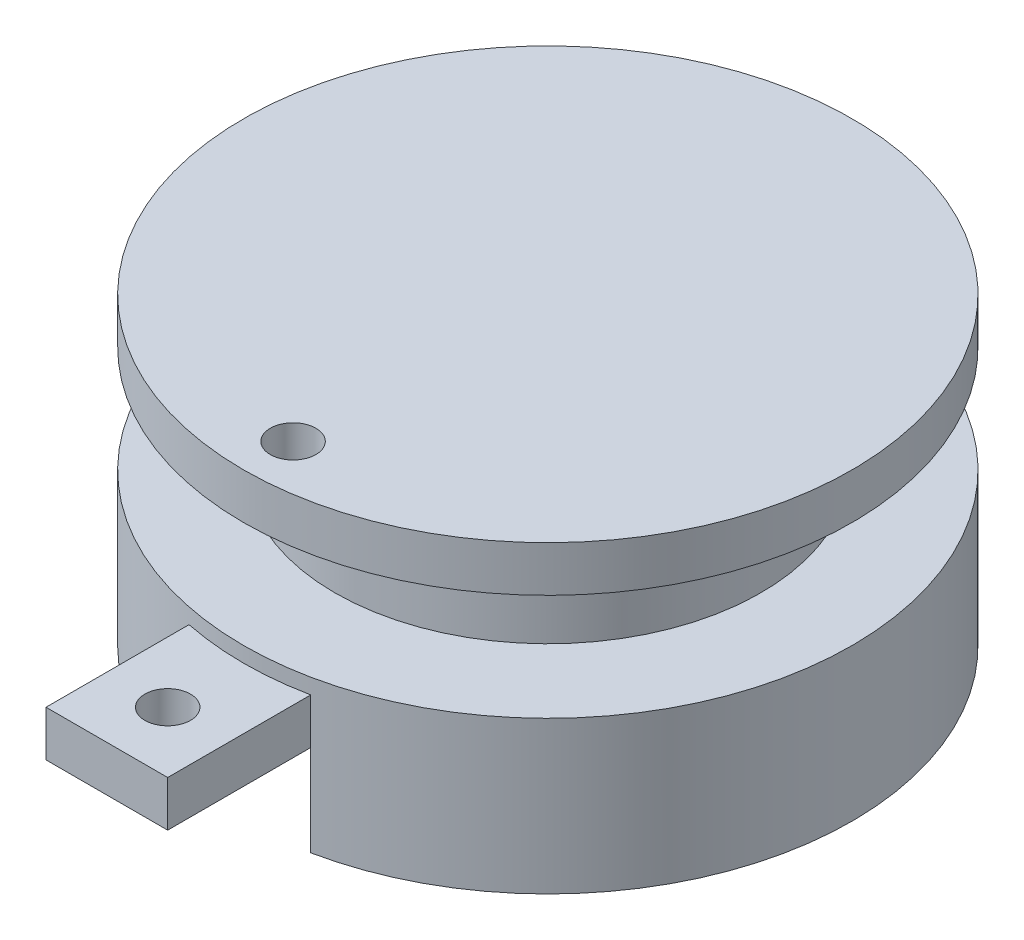
SolidWorks part; units mm, degrees
ref_plane "Front Plane" through (0, 0, 0) normal (0, 0, 1) x (1, 0, 0)
ref_plane "Top Plane" through (0, 0, 0) normal (0, 1, 0) x (1, 0, 0)
ref_plane "Right Plane" through (0, 0, 0) normal (1, 0, 0) x (0, 0, -1)
sketch "Sketch1" plane through (0, 0, 0) normal (0, 1, 0) x (1, 0, 0)
  circle A0 centre (0, 0) radius 20
extrude "Boss-Extrude1" add sketch "Sketch1" along normal blind 10.0023 contours A0
sketch "Sketch2" plane through (0, 0, 0) normal (0, -1, 0) x (1, 0, 0)
  line L0 (-5.2069, 6.0736) -> (-4, 8.2634)
  line L6 (-4, 16.9622) -> (-4, 8.2634)
  line L8 (4, 16.9622) -> (4, 8.2634)
  line L10 (4, 8.2634) -> (5.2069, 6.0736)
  line L13 (4, 16.9622) -> (4, 25.8512)
  line L14 (4, 25.8512) -> (-4, 25.8512)
  line L15 (-4, 16.9622) -> (-4, 25.8512)
  arc A1 (-5.2069, 6.0736) -> (5.2069, 6.0736) centre (0, 0) ccw
  dimension "D1" = 8
  dimension "D2" = 8.6988
extrude "Cut-Extrude1" cut sketch "Sketch2" against normal blind 6
sketch "Sketch3" plane through (0, 10.0023, 0) normal (0, 1, 0) x (1, 0, 0)
  line L0 (18.5, 0) -> (20, 0) construction
  line L2 (14, 0) -> (0, 0) construction
  circle A0 centre (0, 0) radius 18.5
  circle A1 centre (0, 0) radius 20 construction
  circle A2 centre (0, 0) radius 14
  dimension "D1" = 1.5
  dimension "D2" = 14
extrude "Boss-Extrude5" add sketch "Sketch3" along normal blind 10 contours A2
sketch "Sketch11" plane through (0, 20.0023, 0) normal (0, 1, 0) x (1, 0, 0)
  circle A0 centre (0, 0) radius 20
extrude "Boss-Extrude6" add sketch "Sketch11" against normal blind 3
sketch "Sketch12" plane through (0, 20.0023, 0) normal (0, 1, 0) x (1, 0, 0)
  line L0 (0, -20) -> (0, -18.25) construction
  circle A0 centre (0, -16.75) radius 1.5
  circle A1 centre (0, 0) radius 20 construction
  dimension "D1" = 1.75
  dimension "D2" = 3
extrude "Cut-Extrude3" cut sketch "Sketch12" against normal blind 3 contours A0
ref_plane "Plane3" through (0, 0, 20) normal (0, 0, 1) x (1, 0, 0)
sketch "Sketch16" plane through (0, 0, 20) normal (0, 0, 1) x (1, 0, 0)
  line L1 (4.0069, 8.995) -> (4.0069, 5.995)
  line L2 (4.0069, 8.995) -> (-3.9931, 8.995)
  line L4 (4.0069, 5.995) -> (-3.9931, 5.995)
  line L5 (-3.9931, 8.995) -> (-3.9931, 5.995)
  dimension "D1" = 8
  dimension "D2" = 3
extrude "Boss-Extrude7" add sketch "Sketch16" along normal blind 9 and the other way blind 1 contours L2 L5 L4 L1
sketch "Sketch17" plane through (0, 8.995, 0) normal (0, 1, 0) x (1, 0, 0)
  line L0 (0.0069, -29) -> (0.0069, -26.5) construction
  line L2 (0.0069, -23.5) -> (0.007, -20)
  line L3 (4.0069, -29) -> (-3.9931, -29) construction
  circle A0 centre (0.0069, -25) radius 1.5
  arc A2 (-3.9931, -19.5973) -> (4.0069, -19.5945) centre (0, 0) ccw construction
  dimension "D1" = 3.5
  dimension "D3" = 3
extrude "Cut-Extrude4" cut sketch "Sketch17" against normal blind 14
sketch "Sketch19" plane through (0, 6, 0) normal (0, -1, 0) x (1, 0, 0)
  line L1 (8, 0) -> (-8, 0)
  circle A0 centre (0, 0) radius 3.5
  arc A1 (-5.2069, 6.0736) -> (5.2069, 6.0736) centre (0, 0) ccw construction
  arc A2 (-5.2069, 6.0736) -> (5.2069, 6.0736) centre (0, 0) ccw construction
  point P2 (0, 0)
  dimension "D1" = 7
extrude "Cut-Extrude5" cut sketch "Sketch19" against normal blind 2 contours A0
